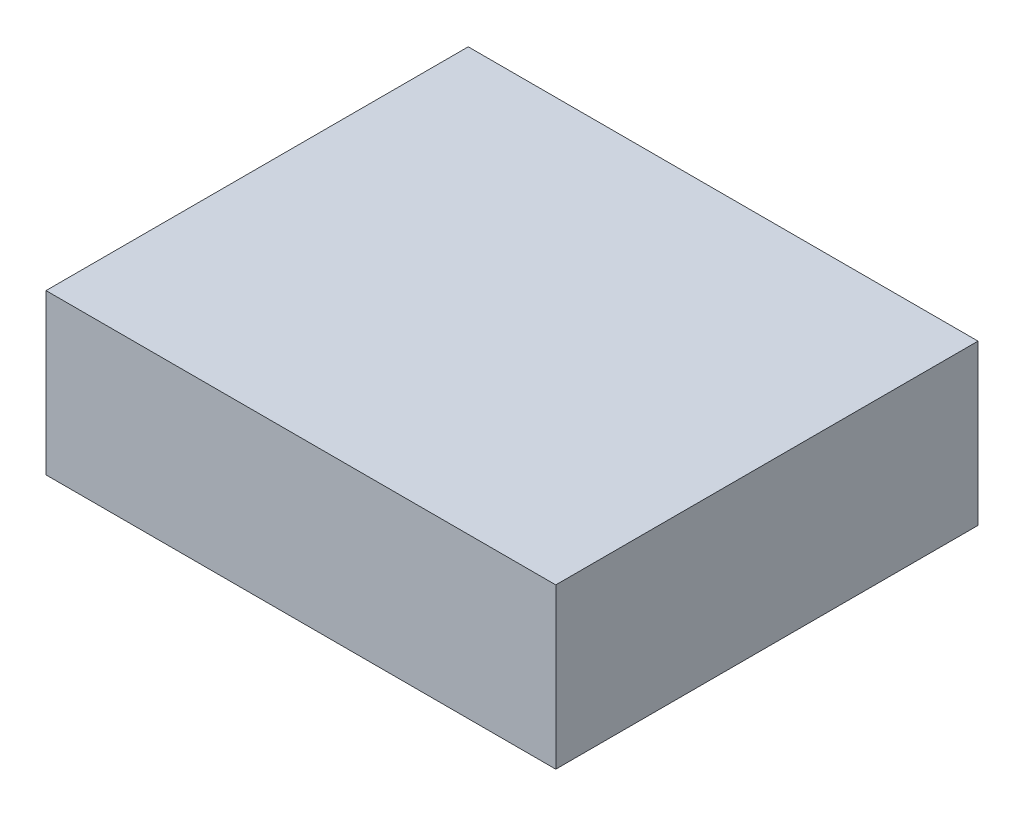
SolidWorks part; units mm, degrees
ref_plane "Front Plane" through (0, 0, 0) normal (0, 0, 1) x (1, 0, 0)
ref_plane "Top Plane" through (0, 0, 0) normal (0, 1, 0) x (1, 0, 0)
ref_plane "Right Plane" through (0, 0, 0) normal (1, 0, 0) x (0, 0, -1)
sketch "Sketch1" plane through (0, 0, 0) normal (0, 1, 0) x (1, 0, 0)
  line L1 (-49.5, -41) -> (49.5, -41)
  line L2 (-49.5, -41) -> (-49.5, 41)
  line L3 (-49.5, 41) -> (49.5, 41)
  line L4 (49.5, -41) -> (49.5, 41)
  line L5 (-49.5, -41) -> (49.5, 41) construction
  line L6 (-49.5, 41) -> (49.5, -41) construction
  point P0 (0, 0)
  dimension "D1" = 99
  dimension "D2" = 82
extrude "Boss-Extrude1" add sketch "Sketch1" along normal blind 31
